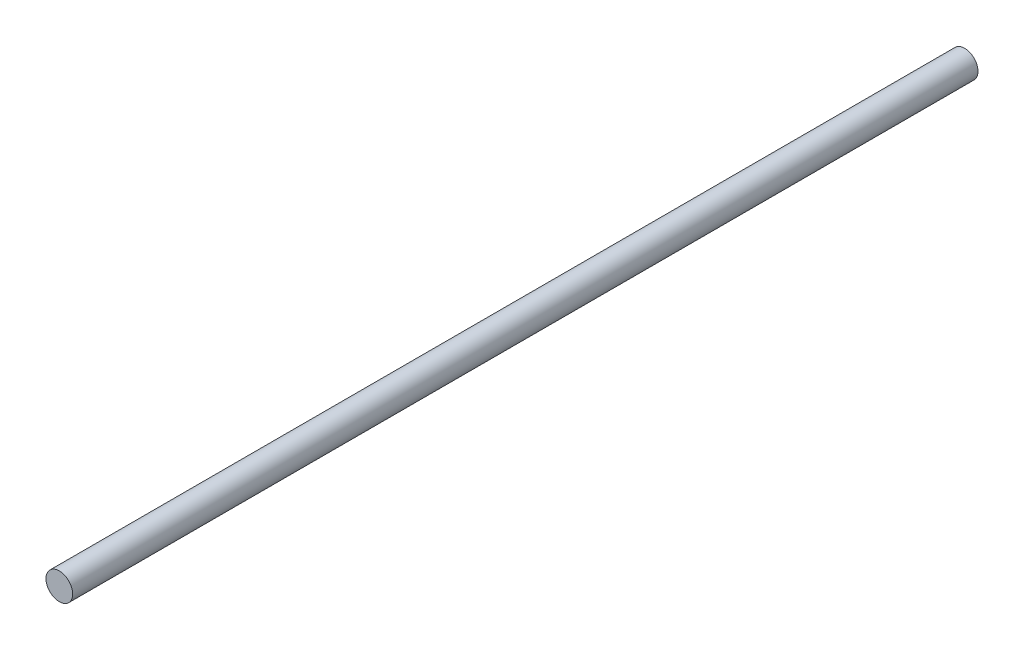
SolidWorks part; units mm, degrees
ref_plane "Front Plane" through (0, 0, 0) normal (0, 0, 1) x (1, 0, 0)
ref_plane "Top Plane" through (0, 0, 0) normal (0, 1, 0) x (1, 0, 0)
ref_plane "Right Plane" through (0, 0, 0) normal (1, 0, 0) x (0, 0, -1)
sketch "CurveSketch" plane through (0, 0, 0) normal (0, 0, 1) x (1, 0, 0)
  circle A0 centre (-3.719, 5.173) radius 0.173
  dimension "D1" = 0.173
extrude "CurveBoss" add sketch "CurveSketch" along normal blind 11.731
